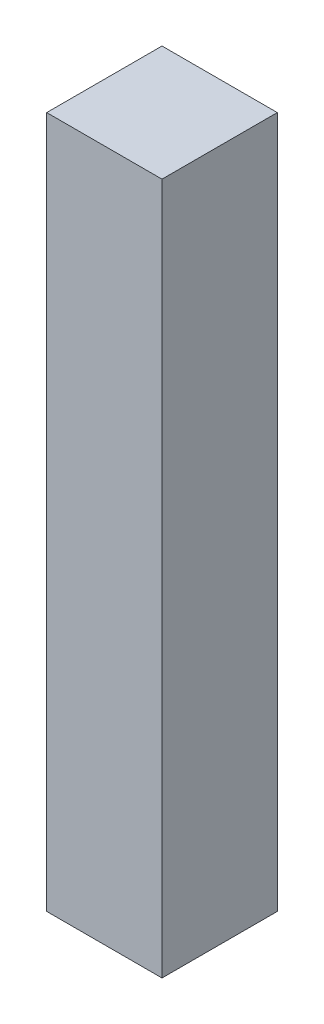
SolidWorks part; units mm, degrees
material "Plain Carbon Steel"
ref_plane "Front Plane" through (0, 0, 0) normal (0, 0, 1) x (1, 0, 0)
ref_plane "Top Plane" through (0, 0, 0) normal (0, 1, 0) x (1, 0, 0)
ref_plane "Right Plane" through (0, 0, 0) normal (1, 0, 0) x (0, 0, -1)
sketch "Sketch1" plane through (0, 0, 0) normal (0, 1, 0) x (1, 0, 0)
  line L1 (25.4, 25.4) -> (-25.4, 25.4)
  line L2 (25.4, 25.4) -> (25.4, -25.4)
  line L3 (25.4, -25.4) -> (-25.4, -25.4)
  line L4 (-25.4, 25.4) -> (-25.4, -25.4)
  line L5 (25.4, 25.4) -> (-25.4, -25.4) construction
  line L6 (25.4, -25.4) -> (-25.4, 25.4) construction
  point P0 (0, 0)
  dimension "D1" = 50.8
extrude "Boss-Extrude1" add sketch "Sketch1" along normal mid plane 304.8
equation "\"box side\"= 2in"
equation "\"box length\"= 12in"
equation "\"D1@Sketch1\"=\"box side\""
equation "\"D1@Boss-Extrude1\"=\"box length\""
